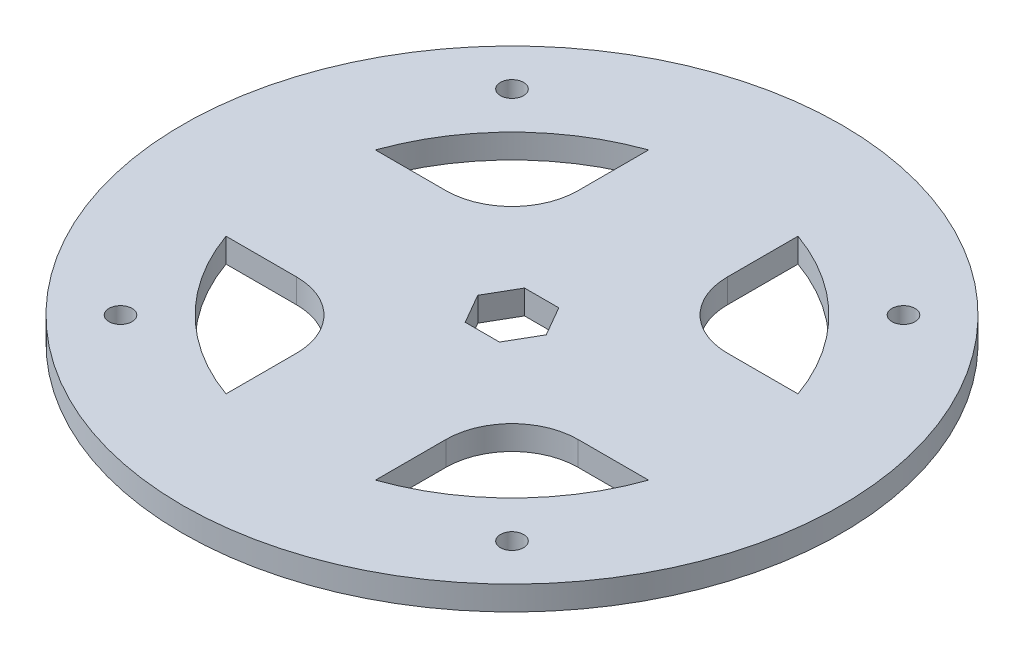
SolidWorks part; units mm, degrees
ref_plane "Front Plane" through (0, 0, 0) normal (0, 0, 1) x (1, 0, 0)
ref_plane "Top Plane" through (0, 0, 0) normal (0, 1, 0) x (1, 0, 0)
ref_plane "Right Plane" through (0, 0, 0) normal (1, 0, 0) x (0, 0, -1)
sketch "Sketch1" plane through (0, 0, 0) normal (0, 1, 0) x (1, 0, 0)
  circle A0 centre (0, 0) radius 75
  circle A1 centre (0, 0) radius 4.25
  dimension "D1" = 150
  dimension "D2" = 8.5
extrude "Boss-Extrude1" add sketch "Sketch1" along normal blind 5.5
sketch "Sketch4" plane through (0, 5.5, 0) normal (0, 1, 0) x (1, 0, 0)
  line L0 (0, 0) -> (-44.5477, 44.5477) construction
  line L1 (0, 0) -> (-44.5477, -44.5477) construction
  line L2 (0, 0) -> (44.5477, -44.5477) construction
  line L3 (0, 0) -> (44.5477, 44.5477) construction
  line L5 (7.7942, 0) -> (3.8971, 6.75)
  line L6 (3.8971, 6.75) -> (-3.8971, 6.75)
  line L7 (-3.8971, 6.75) -> (-7.7942, 0)
  line L8 (-7.7942, 0) -> (-3.8971, -6.75)
  line L9 (-3.8971, -6.75) -> (3.8971, -6.75)
  line L10 (3.8971, -6.75) -> (7.7942, 0)
  circle A0 centre (0, 0) radius 63 construction
  circle A1 centre (44.5477, -44.5477) radius 2.625
  circle A2 centre (-44.5477, -44.5477) radius 2.625
  circle A3 centre (44.5477, 44.5477) radius 2.625
  circle A4 centre (-44.5477, 44.5477) radius 2.625
  circle A5 centre (0, 0) radius 6.75 construction
  circle A6 centre (0, 0) radius 75 construction
  dimension "D1" = 126
  dimension "D2" = 5.25
  dimension "D3" = 13.5
extrude "Cut-Extrude2" cut sketch "Sketch4" against normal up to surface (5.5 mm away) up to face at (0, 0, 75)
sketch "Sketch5" plane through (0, 5.5, 0) normal (0, 1, 0) x (1, 0, 0)
  line L11 (32, -17) -> (48.0833, -17)
  line L12 (17, -32) -> (17, -48.0833)
  line L19 (0, 0) -> (0, -22.6064) construction
  line L20 (0, 0) -> (-26.2616, 0) construction
  line L21 (-17, -32) -> (-17, -48.0833)
  line L22 (-32, -17) -> (-48.0833, -17)
  line L23 (17, 32) -> (17, 48.0833)
  line L24 (32, 17) -> (48.0833, 17)
  line L25 (-32, 17) -> (-48.0833, 17)
  line L26 (-17, 32) -> (-17, 48.0833)
  arc A16 (17, -48.0833) -> (48.0833, -17) centre (0, 0) ccw
  arc A17 (32, -17) -> (17, -32) centre (32, -32) ccw
  arc A18 (-32, -17) -> (-17, -32) centre (-32, -32) cw
  arc A19 (-17, -48.0833) -> (-48.0833, -17) centre (0, 0) cw
  arc A20 (32, 17) -> (17, 32) centre (32, 32) cw
  arc A21 (17, 48.0833) -> (48.0833, 17) centre (0, 0) cw
  arc A22 (-17, 48.0833) -> (-48.0833, 17) centre (0, 0) ccw
  arc A23 (-32, 17) -> (-17, 32) centre (-32, 32) ccw
  dimension "D1" = 102
extrude "Cut-Extrude3" cut sketch "Sketch5" against normal up to surface (5.5 mm away) up to face at (-44.5477, 0, 47.1727)
